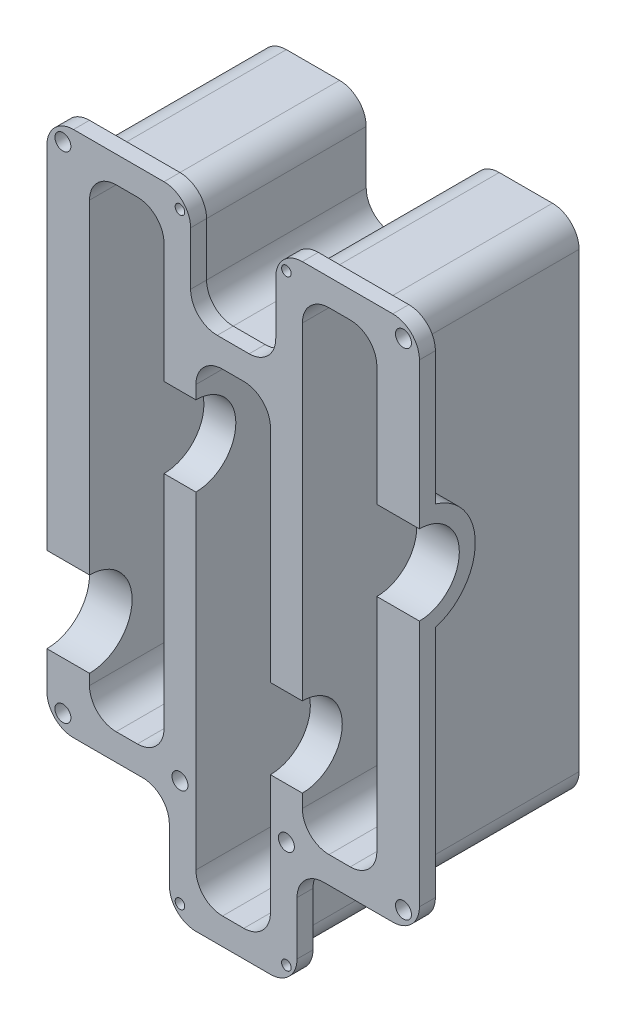
SolidWorks part; units mm, degrees
material "Alloy Steel (SS)"
ref_plane "Front " through (0, 0, 0) normal (0, 0, 1) x (1, 0, 0)
ref_plane "Top " through (0, 0, 0) normal (0, 1, 0) x (1, 0, 0)
ref_plane "Right " through (0, 0, 0) normal (1, 0, 0) x (0, 0, -1)
sketch "Sketch1" plane through (0, 0, 0) normal (0, 0, 1) x (1, 0, 0)
  line L1 (-35, 59.5) -> (35, 59.5)
  line L2 (-35, 59.5) -> (-35, -59.5)
  line L3 (-35, -59.5) -> (35, -59.5)
  line L4 (35, 59.5) -> (35, -59.5)
  line L5 (-35, 59.5) -> (35, -59.5) construction
  line L6 (-35, -59.5) -> (35, 59.5) construction
  point P0 (0, 0)
  dimension "D1" = 119
  dimension "D2" = 70
extrude "Boss-Extrude1" add sketch "Sketch1" along normal blind 35
sketch "Sketch2" plane through (-35, 0, 0) normal (-1, 0, 0) x (0, 0, 1)
  line L0 (35, 59.5) -> (35, -59.5) construction
  line L1 (35, -59.5) -> (0, -59.5) construction
  circle A0 centre (35, -19.5) radius 8
  dimension "D1" = 40
  dimension "D2" = 16
extrude "Cut-Extrude1" cut sketch "Sketch2" against normal blind 8
sketch "Sketch3" plane through (0, 0, 35) normal (0, 0, 1) x (1, 0, 0)
  line L0 (-35, 59.5) -> (-35, -11.5) construction
  line L1 (-27, -34.5) -> (-13, -34.5)
  line L2 (-27, -34.5) -> (-27, 54.5)
  line L3 (-27, 54.5) -> (-13, 54.5)
  line L4 (-13, -34.5) -> (-13, 12)
  line L5 (-7, 34.5) -> (7, 34.5)
  line L6 (-7, 34.5) -> (-7, 27)
  line L7 (-7, -54.5) -> (7, -54.5)
  line L8 (7, 34.5) -> (7, -12)
  line L9 (13, 54.5) -> (27, 54.5)
  line L10 (13, 54.5) -> (13, -12)
  line L11 (13, -34.5) -> (27, -34.5)
  line L12 (27, 54.5) -> (27, -34.5)
  line L13 (-35, -19.5) -> (76.7799, -19.5) construction
  line L14 (-35, 19.5) -> (90.1486, 19.5) construction
  line L15 (-35, -11.5) -> (-35, -27.5) construction
  line L16 (-13, 27) -> (-7, 27)
  line L17 (-13, 12) -> (-7, 12)
  line L18 (-13, 27) -> (-13, 54.5)
  line L19 (-7, 12) -> (-7, -54.5)
  line L20 (7, -27) -> (13, -27)
  line L21 (13, -12) -> (7, -12)
  line L22 (13, -27) -> (13, -34.5)
  line L23 (7, -27) -> (7, -54.5)
  line L24 (35, -59.5) -> (35, 59.5) construction
  dimension "D1" = 8
  dimension "D2" = 14
  dimension "D3" = 6
  dimension "D4" = 6
  dimension "D5" = 15
  dimension "D6" = 39
  dimension "D7" = 89
  dimension "D8" = 15
  dimension "D9" = 7.5
  dimension "D10" = 15
  dimension "D11" = 7.5
  dimension "D12" = 15
  dimension "D13" = 89
  dimension "D14" = 8
extrude "Cut-Extrude2" cut sketch "Sketch3" against normal blind 32
sketch "Sketch4" plane through (35, 0, 0) normal (1, 0, 0) x (0, 0, -1)
  line L0 (-35, -59.5) -> (-35, 59.5) construction
  line L1 (-35, -59.5) -> (0, -59.5) construction
  circle A0 centre (-35, 19.5) radius 7.5
  dimension "D1" = 15
  dimension "D2" = 79
extrude "Cut-Extrude3" cut sketch "Sketch4" against normal blind 8
sketch "Sketch5" plane through (0, 0, 35) normal (0, 0, 1) x (1, 0, 0)
  line L0 (35, 59.5) -> (-35, 59.5) construction
  line L1 (-8, 59.5) -> (8, 59.5)
  line L2 (-8, 59.5) -> (-8, 39.5)
  line L3 (-8, 39.5) -> (8, 39.5)
  line L4 (8, 59.5) -> (8, 39.5)
  line L5 (-35, -59.5) -> (35, -59.5) construction
  line L6 (12, -59.5) -> (35, -59.5)
  line L7 (12, -59.5) -> (12, -39.5)
  line L8 (12, -39.5) -> (35, -39.5)
  line L9 (35, -59.5) -> (35, -39.5)
  line L10 (35, -59.5) -> (35, 12) construction
  line L11 (-35, -27.5) -> (-35, -59.5) construction
  line L12 (-35, -39.5) -> (-12, -39.5)
  line L13 (-35, -39.5) -> (-35, -59.5)
  line L14 (-35, -59.5) -> (-12, -59.5)
  line L15 (-12, -39.5) -> (-12, -59.5)
  line L16 (13, -34.5) -> (27, -34.5) construction
  line L17 (7, -54.5) -> (7, -27) construction
  line L18 (-7, 12) -> (-7, -54.5) construction
  line L19 (-27, -34.5) -> (-13, -34.5) construction
  line L20 (-13, 27) -> (-13, 54.5) construction
  line L21 (13, 54.5) -> (13, -12) construction
  line L22 (7, 34.5) -> (-7, 34.5) construction
  dimension "D1" = 5
  dimension "D2" = 5
  dimension "D3" = 5
  dimension "D4" = 5
  dimension "D5" = 5
  dimension "D6" = 5
  dimension "D7" = 5
extrude "Cut-Extrude4" cut sketch "Sketch5" against normal through all
sketch "Sketch6" plane through (-35, 0, 0) normal (-1, 0, 0) x (0, 0, 1)
  line L4 (32, 59.5) -> (0, 59.5)
  line L5 (0, 59.5) -> (0, -39.5)
  line L6 (32, -30.083) -> (32, -39.5)
  line L7 (32, 59.5) -> (32, -8.917)
  line L8 (32, -30.083) -> (32, -39.5)
  line L9 (32, 59.5) -> (32, -8.917)
  line L10 (0, -39.5) -> (32, -39.5)
  arc A3 (32, -8.917) -> (32, -30.083) centre (35, -19.5) ccw
  arc A4 (32, -8.917) -> (32, -30.083) centre (35, -19.5) ccw
  dimension "D1" = 3
extrude "Cut-Extrude5" cut sketch "Sketch6" against normal blind 5
sketch "Sketch7" plane through (0, -39.5, 0) normal (0, -1, 0) x (1, 0, 0)
  line L1 (-30, 32) -> (-12, 32)
  line L2 (-30, 32) -> (-30, 0)
  line L3 (-30, 0) -> (-12, 0)
  line L4 (-12, 32) -> (-12, 0)
extrude "Cut-Extrude6" cut sketch "Sketch7" against normal blind 2
sketch "Sketch8" plane through (-12, 0, 0) normal (-1, 0, 0) x (0, 0, 1)
  line L1 (32, -37.5) -> (0, -37.5)
  line L2 (32, -37.5) -> (32, -59.5)
  line L3 (32, -59.5) -> (0, -59.5)
  line L4 (0, -37.5) -> (0, -59.5)
extrude "Cut-Extrude7" cut sketch "Sketch8" against normal blind 2
sketch "Sketch9" plane through (0, -59.5, 0) normal (0, -1, 0) x (1, 0, 0)
  line L1 (-10, 32) -> (12, 32)
  line L2 (-10, 32) -> (-10, 0)
  line L3 (-10, 0) -> (12, 0)
  line L4 (12, 32) -> (12, 0)
extrude "Cut-Extrude8" cut sketch "Sketch9" against normal blind 2
sketch "Sketch10" plane through (12, 0, 0) normal (1, 0, 0) x (0, 0, -1)
  line L1 (-32, -57.5) -> (0, -57.5)
  line L2 (-32, -57.5) -> (-32, -39.5)
  line L3 (-32, -39.5) -> (0, -39.5)
  line L4 (0, -57.5) -> (0, -39.5)
extrude "Cut-Extrude9" cut sketch "Sketch10" against normal blind 2
sketch "Sketch11" plane through (0, -39.5, 0) normal (0, -1, 0) x (1, 0, 0)
  line L1 (10, 32) -> (35, 32)
  line L2 (10, 32) -> (10, 0)
  line L3 (10, 0) -> (35, 0)
  line L4 (35, 32) -> (35, 0)
extrude "Cut-Extrude10" cut sketch "Sketch11" against normal blind 2
sketch "Sketch12" plane through (35, 0, 0) normal (1, 0, 0) x (0, 0, -1)
  line L4 (-32, 59.5) -> (0, 59.5)
  line L5 (0, 59.5) -> (0, -37.5)
  line L6 (-32, -39.5) -> (-32, 9.4377)
  line L7 (-32, 29.5623) -> (-32, 59.5)
  line L8 (-32, -37.5) -> (-32, 9.4377)
  line L9 (-32, 29.5623) -> (-32, 59.5)
  line L10 (0, -37.5) -> (-32, -37.5)
  arc A3 (-32, 9.4377) -> (-32, 29.5623) centre (-35, 19.5) ccw
  arc A4 (-32, 9.4377) -> (-32, 29.5623) centre (-35, 19.5) ccw
  dimension "D1" = 3
extrude "Cut-Extrude11" cut sketch "Sketch12" against normal blind 5
sketch "Sketch13" plane through (0, 59.5, 0) normal (0, 1, 0) x (1, 0, 0)
  line L1 (30, -32) -> (8, -32)
  line L2 (30, -32) -> (30, 0)
  line L3 (30, 0) -> (8, 0)
  line L4 (8, -32) -> (8, 0)
  line L5 (-30, -32) -> (-8, -32)
  line L6 (-30, -32) -> (-30, 0)
  line L7 (-30, 0) -> (-8, 0)
  line L8 (-8, -32) -> (-8, 0)
extrude "Cut-Extrude12" cut sketch "Sketch13" against normal blind 2
sketch "Sketch14" plane through (8, 0, 0) normal (-1, 0, 0) x (0, 0, 1)
  line L1 (32, 57.5) -> (0, 57.5)
  line L2 (32, 57.5) -> (32, 39.5)
  line L3 (32, 39.5) -> (0, 39.5)
  line L4 (0, 57.5) -> (0, 39.5)
extrude "Cut-Extrude13" cut sketch "Sketch14" against normal blind 2
sketch "Sketch15" plane through (0, 39.5, 0) normal (0, 1, 0) x (1, 0, 0)
  line L1 (10, -32) -> (-8, -32)
  line L2 (10, -32) -> (10, 0)
  line L3 (10, 0) -> (-8, 0)
  line L4 (-8, -32) -> (-8, 0)
extrude "Cut-Extrude14" cut sketch "Sketch15" against normal blind 2
sketch "Sketch16" plane through (-8, 0, 0) normal (1, 0, 0) x (0, 0, -1)
  line L1 (-32, 37.5) -> (0, 37.5)
  line L2 (-32, 37.5) -> (-32, 57.5)
  line L3 (-32, 57.5) -> (0, 57.5)
  line L4 (0, 37.5) -> (0, 57.5)
extrude "Cut-Extrude15" cut sketch "Sketch16" against normal blind 2
fillet "Fillet1" radius 5 12 edges at (13, 54.5, 19) (-7, 34.5, 19) (-27, 54.5, 19) (-13, 54.5, 19) (7, 34.5, 19) (27, 54.5, 19) (-27, -34.5, 19) (-7, -54.5, 19) (13, -34.5, 19) (-13, -34.5, 19) (7, -54.5, 19) (27, -34.5, 19)
fillet "Fillet3" radius 5 12 edges at (-30, 57.5, 16) (10, 37.5, 16) (-10, 37.5, 16) (-10, 57.5, 16) (10, 57.5, 16) (30, 57.5, 16) (-30, -37.5, 16) (-10, -37.5, 16) (-10, -57.5, 16) (10, -57.5, 16) (10, -37.5, 16) (30, -37.5, 16)
fillet "Fillet4" radius 5 12 edges at (8, 39.5, 33.5) (-35, 59.5, 33.5) (8, 59.5, 33.5) (-8, 39.5, 33.5) (-8, 59.5, 33.5) (35, 59.5, 33.5) (12, -39.5, 33.5) (35, -39.5, 33.5) (12, -59.5, 33.5) (-12, -59.5, 33.5) (-12, -39.5, 33.5) (-35, -39.5, 33.5)
sketch "Sketch17" plane through (0, 0, 35) normal (0, 0, 1) x (1, 0, 0)
  line L0 (-13, 59.5) -> (-30, 59.5) construction
  line L1 (-32, 56.5) -> (32, 56.5) construction
  line L2 (-32, 56.5) -> (-32, -36.5) construction
  line L3 (-32, -36.5) -> (32, -36.5) construction
  line L4 (32, 56.5) -> (32, -36.5) construction
  line L5 (-35, 54.5) -> (-35, -11.5) construction
  line L6 (-7, 12) -> (-7, -49.5) construction
  line L7 (7, -49.5) -> (7, -27) construction
  circle A0 centre (-32, 56.5) radius 1.5
  circle A1 centre (32, 56.5) radius 1.5
  circle A2 centre (32, -36.5) radius 1.5
  circle A3 centre (-32, -36.5) radius 1.5
  circle A4 centre (-10, -36.5) radius 1.5
  circle A5 centre (10, -36.5) radius 1.5
  dimension "D5" = 3
  dimension "D7" = 3
  dimension "D1" = 93
  dimension "D2" = 64
  dimension "D3" = 3
  dimension "D4" = 3
  dimension "D6" = 3
extrude "Cut-Extrude16" cut sketch "Sketch17" against normal blind 10
sketch "Sketch18" plane through (0, 0, 35) normal (0, 0, 1) x (1, 0, 0)
  line L1 (-10, 56.5) -> (10, 56.5) construction
  line L2 (-10, 56.5) -> (-10, -56.5) construction
  line L3 (-10, -56.5) -> (10, -56.5) construction
  line L4 (10, 56.5) -> (10, -56.5) construction
  line L5 (-13, 59.5) -> (-30, 59.5) construction
  line L6 (-8, 54.5) -> (-8, 44.5) construction
  circle A0 centre (-10, 56.5) radius 0.9
  circle A1 centre (10, 56.5) radius 0.9
  circle A2 centre (-10, -56.5) radius 0.9
  circle A3 centre (10, -56.5) radius 0.9
  dimension "D5" = 1.8
  dimension "D1" = 113
  dimension "D2" = 20
  dimension "D3" = 2
  dimension "D4" = 3
extrude "Cut-Extrude17" cut sketch "Sketch18" against normal blind 10
sketch "Sketch19" plane through (-13, 0, 0) normal (-1, 0, 0) x (0, 0, 1)
  line L0 (35, 27) -> (3, 27)
  line L1 (3, 27) -> (35, 27) construction
  line L2 (3, 27) -> (3, 12)
  line L3 (3, 12) -> (35, 12) construction
  line L4 (3, 12) -> (35, 12)
  arc A0 (35, 27) -> (35, 12) centre (35, 19.5) ccw
  dimension "D1" = 15
  dimension "D2" = 32
extrude "Boss-Extrude2" add sketch "Sketch19" against normal blind 6
sketch "Sketch20" plane through (7, 0, 0) normal (-1, 0, 0) x (0, 0, 1)
  line L0 (35, -12) -> (3, -12)
  line L1 (3, -12) -> (3, -27)
  line L2 (3, -27) -> (35, -27)
  arc A0 (35, -12) -> (35, -27) centre (35, -19.5) ccw
  dimension "D1" = 15
  dimension "D2" = 32
extrude "Boss-Extrude3" add sketch "Sketch20" against normal blind 6
